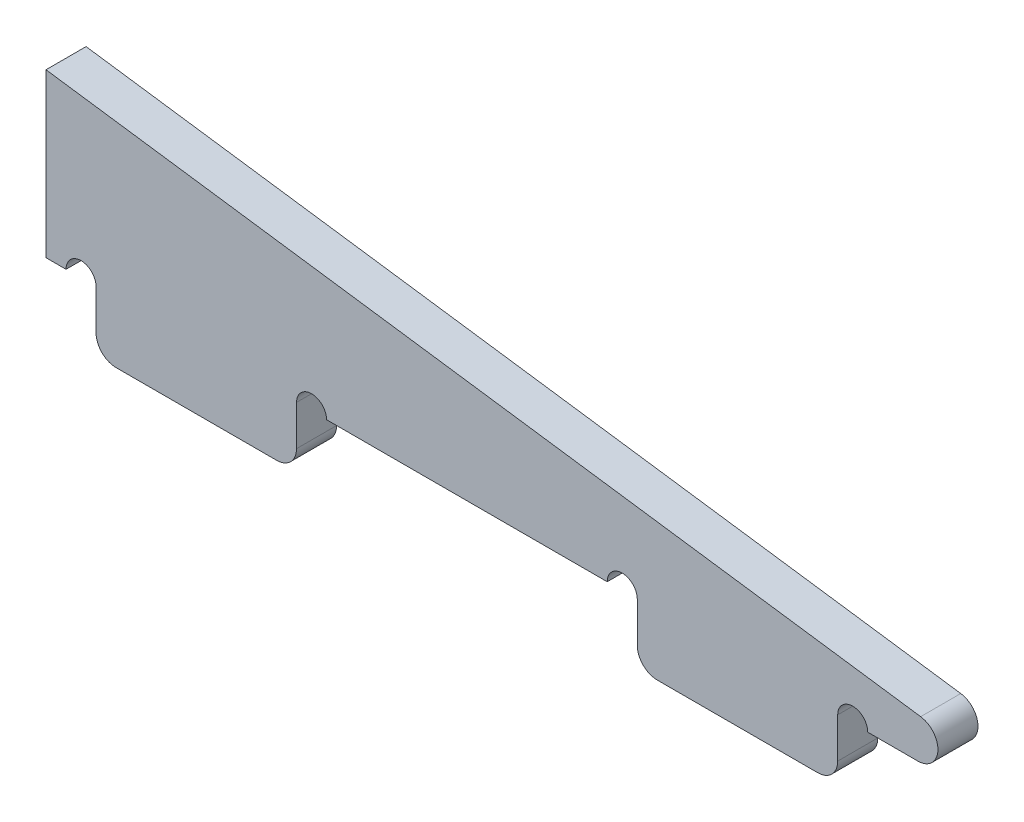
SolidWorks part; units mm, degrees
material "Thornel Mat VMA"
ref_plane "前视基准面" through (0, 0, 0) normal (0, 0, 1) x (1, 0, 0)
ref_plane "上视基准面" through (0, 0, 0) normal (0, 1, 0) x (1, 0, 0)
ref_plane "右视基准面" through (0, 0, 0) normal (1, 0, 0) x (0, 0, -1)
sketch "草图1" plane through (0, 0, 0) normal (0, 0, 1) x (1, 0, 0)
  line L0 (4.1392, 1.9903) -> (-39.5, 8.1234)
  line L1 (-39.5, 8.1234) -> (-39.5, 0)
  line L2 (-39.5, 0) -> (-37, 0)
  line L3 (-37, 0) -> (-37, -3)
  line L4 (-37, -3) -> (-27, -3)
  line L5 (-27, -3) -> (-27, 0)
  line L6 (-27, 0) -> (-10, 0)
  line L7 (-10, 0) -> (-10, -3)
  line L8 (-10, -3) -> (0, -3)
  line L9 (0, -3) -> (0, 0)
  line L10 (0, 0) -> (4, 0)
  arc A0 (4, 0) -> (4.1392, 1.9903) centre (4, 1) ccw
  dimension "D6" = 1
  dimension "D1" = 3
  dimension "D2" = 10
  dimension "D3" = 17
  dimension "D4" = 2.5
  dimension "D5" = 8
  dimension "D7" = 4
extrude "凸台-拉伸1" add sketch "草图1" along normal blind 2
sketch "草图2" plane through (0, 0, 2) normal (0, 0, 1) x (1, 0, 0)
  line L0 (-39.5, 0) -> (-37, 0) construction
  line L1 (-27, 0) -> (-10, 0) construction
  line L2 (0, 0) -> (4, 0) construction
  circle A0 centre (-37.75, 0) radius 0.75
  circle A1 centre (-26.25, 0) radius 0.75
  circle A2 centre (-10.75, 0) radius 0.75
  circle A3 centre (0.75, 0) radius 0.75
  dimension "D1" = 1.5
extrude "切除-拉伸1" cut sketch "草图2" against normal through all
fillet "圆角1" radius 1 4 edges at (0, -3, 1) (-10, -3, 1) (-27, -3, 1) (-37, -3, 1)
